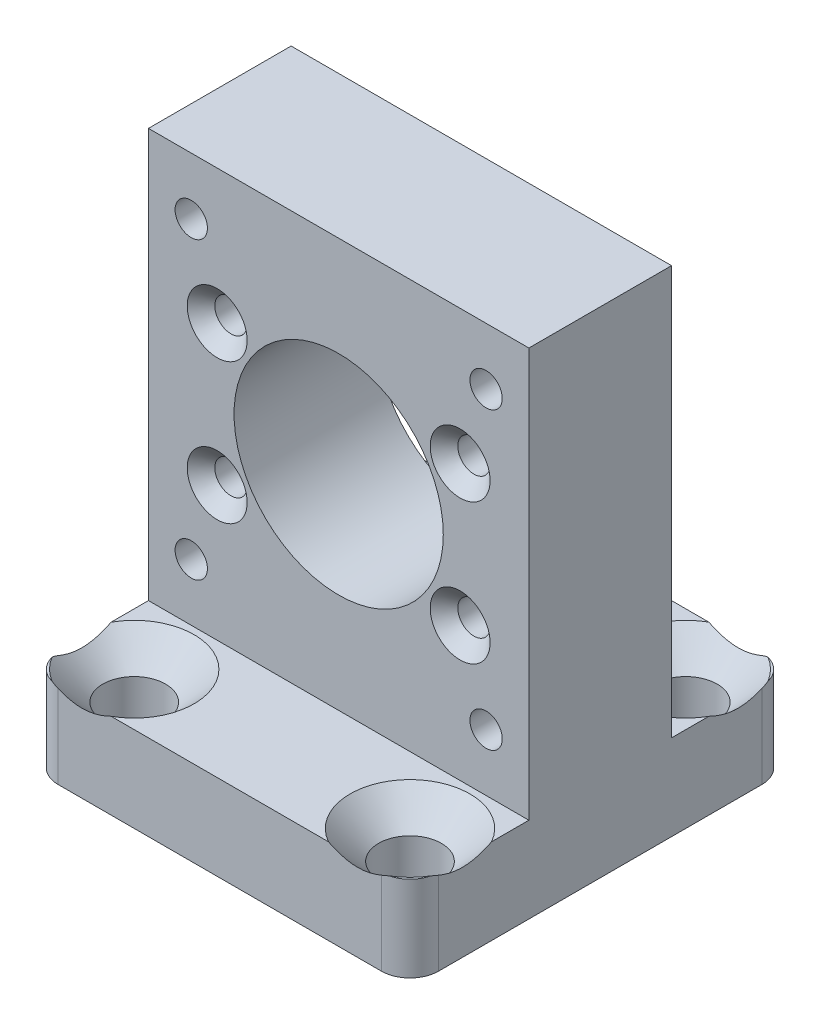
SolidWorks part; units mm, degrees
material "3.1355 (EN-AW 2024)"
ref_plane "Front" through (0, 0, 0) normal (0, 0, 1) x (1, 0, 0)
ref_plane "Top" through (0, 0, 0) normal (0, 1, 0) x (1, 0, 0)
ref_plane "Right" through (0, 0, 0) normal (1, 0, 0) x (0, 0, -1)
sketch "Эскиз1" plane through (0, 0, 0) normal (0, 0, 1) x (1, 0, 0)
  line L1 (-20, 21.5) -> (20, 21.5)
  line L2 (-20, 21.5) -> (-20, -21.5)
  line L3 (-20, -21.5) -> (20, -21.5)
  line L4 (20, 21.5) -> (20, -21.5)
  line L5 (-20, 21.5) -> (20, -21.5) construction
  line L6 (-20, -21.5) -> (20, 21.5) construction
  point P0 (0, 0)
  dimension "D1" = 40
  dimension "D2" = 43
extrude "База" add sketch "Эскиз1" against normal mid plane 15
hole_wizard "КреплениеNema17-M3" positions "Эскиз3" profile "Эскиз4" countersink size "M3" standard "ISO" end condition through all
sketch "Эскиз3" plane through (0, 0, -7.5) normal (0, 0, -1) x (-1, 0, 0)
  line L0 (-15.5, 15.5) -> (0, 15.5) construction
  line L1 (0, 15.5) -> (15.5, 15.5) construction
  line L2 (15.5, 15.5) -> (15.5, 0) construction
  line L3 (15.5, 0) -> (15.5, -15.5) construction
  point P0 (-15.5, 15.5)
  point P2 (15.5, 15.5)
  point P4 (15.5, -15.5)
  point P6 (-15.5, -15.5)
  dimension "D1" = 31
  dimension "D2" = 31
sketch "Эскиз4" plane through (15.5, 15.5, -7.5) normal (1, 0, 0) x (0, 1, 0)
  line L0 (0, 0) -> (0, 15)
  line L1 (0, 15) -> (1.7, 15)
  line L2 (1.7, 15) -> (1.7, 1.45)
  line L3 (1.7, 1.45) -> (3.15, 0)
  line L5 (3.15, 0) -> (0, 0)
  line L6 (-1.7, 1.45) -> (-3.15, 0) construction
  line L11 (0, -6.35) -> (0, 107.95) construction
  dimension "Диаметр сквозного отверстия" = 3.4
  dimension "Глубина сквозного отверстия" = 15
  dimension "Диаметр передней зенковки" = 6.3
  dimension "Угол передней зенковки" = 90
sketch "Эскиз8" plane through (0, 0, 7.5) normal (0, 0, 1) x (1, 0, 0)
  circle A0 centre (0, 0) radius 11
  dimension "D1" = 22
extrude "Вырез1" cut sketch "Эскиз8" against normal through all
sketch "Эскиз12" plane through (0, -21.5, 0) normal (0, -1, 0) x (1, 0, 0)
  line L1 (-20, -20) -> (20, -20)
  line L2 (-20, -20) -> (-20, 20)
  line L3 (-20, 20) -> (20, 20)
  line L4 (20, -20) -> (20, 20)
  line L5 (20, -7.5) -> (20, 7.5) construction
  point P5 (0, 20)
  point P7 (20, 0)
  point P9 (20, 0)
  dimension "D2" = 40
extrude "Бобышка-Вытянуть1" add sketch "Эскиз12" along normal blind 9
fillet "Скругление1" radius 3 4 edges at (-20, -26, -20) (-20, -26, 20) (20, -26, -20) (20, -26, 20)
hole_wizard "КреплениеКронштейна-M6" positions "Эскиз18" profile "Эскиз19" countersink size "M6" standard "ISO" end condition through all
sketch "Эскиз18" plane through (0, -21.5, 0) normal (0, 1, 0) x (1, 0, 0)
  line L0 (-14.5, 14.5) -> (0, 14.5) construction
  line L1 (0, 14.5) -> (14.5, 14.5) construction
  line L2 (14.5, 14.5) -> (14.5, 0) construction
  line L3 (14.5, 0) -> (14.5, -14.5) construction
  point P0 (-14.5, -14.5)
  point P2 (14.5, -14.5)
  point P4 (14.5, 14.5)
  point P6 (-14.5, 14.5)
  dimension "D1" = 29
  dimension "D2" = 29
sketch "Эскиз19" plane through (-14.5, -21.5, 14.5) normal (1, 0, 0) x (0, 0, 1)
  line L0 (0, 0) -> (0, 9)
  line L1 (0, 9) -> (3.3, 9)
  line L2 (3.3, 9) -> (3.3, 3)
  line L3 (3.3, 3) -> (6.3, 0)
  line L5 (6.3, 0) -> (0, 0)
  line L6 (-3.3, 3) -> (-6.3, 0) construction
  line L11 (0, -6.35) -> (0, 107.95) construction
  dimension "Диаметр сквозного отверстия" = 6.6
  dimension "Глубина сквозного отверстия" = 9
  dimension "Диаметр передней зенковки" = 12.6
  dimension "Угол передней зенковки" = 90
hole_wizard "КреплениеБлокаПодшипниковM3" positions "Эскиз21" profile "Эскиз22" countersink size "M3" standard "ISO" end condition through all
sketch "Эскиз21" plane through (0, 0, 7.5) normal (0, 0, 1) x (1, 0, 0)
  circle A0 centre (0, 0) radius 14.75 construction
  point P0 (-12.7739, 7.375)
  point P2 (12.7739, 7.375)
  point P4 (12.7739, -7.375)
  point P6 (-12.7739, -7.375)
  dimension "D1" = 29.5
  dimension "D2" = 60
sketch "Эскиз22" plane through (-12.7739, 7.375, 7.5) normal (1, 0, 0) x (0, -1, 0)
  line L0 (0, 0) -> (0, 27.5)
  line L1 (0, 27.5) -> (1.7, 27.5)
  line L2 (1.7, 27.5) -> (1.7, 1.45)
  line L3 (1.7, 1.45) -> (3.15, 0)
  line L5 (3.15, 0) -> (0, 0)
  line L6 (-1.7, 1.45) -> (-3.15, 0) construction
  line L11 (0, -6.35) -> (0, 107.95) construction
  dimension "Диаметр сквозного отверстия" = 3.4
  dimension "Глубина сквозного отверстия" = 27.5
  dimension "Диаметр передней зенковки" = 6.3
  dimension "Угол передней зенковки" = 90
